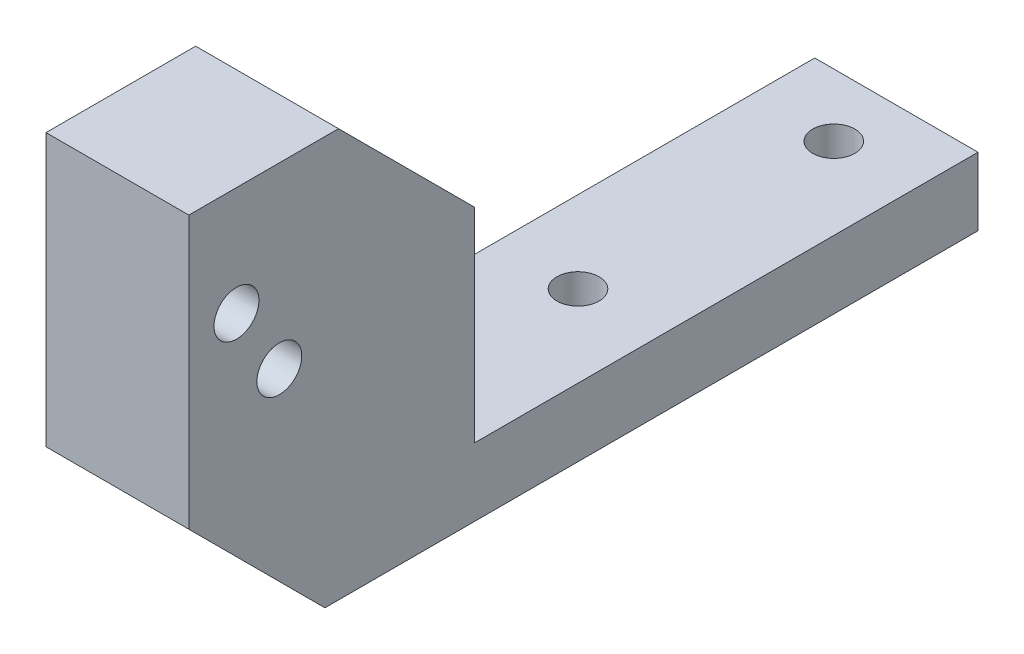
SolidWorks part; units mm, degrees
ref_plane "前视基准面" through (0, 0, 0) normal (0, 0, 1) x (1, 0, 0)
ref_plane "上视基准面" through (0, 0, 0) normal (0, 1, 0) x (1, 0, 0)
ref_plane "右视基准面" through (0, 0, 0) normal (1, 0, 0) x (0, 0, -1)
sketch "草图1" plane through (0, 0, 0) normal (0, 1, 0) x (1, 0, 0)
  line L0 (-55, 0) -> (55, 0) construction
  line L1 (-6, -14) -> (6, -14)
  line L2 (-6, -14) -> (-6, 14)
  line L3 (-6, 14) -> (6, 14)
  line L4 (6, -14) -> (6, 14)
  line L5 (-6, -14) -> (6, 14) construction
  line L6 (-6, 14) -> (6, -14) construction
  circle A0 centre (0, 9.4) radius 1.55
  circle A1 centre (0, -9.4) radius 1.55
  point P0 (0, 0)
  dimension "D3" = 18.8
  dimension "D4" = 3.1
  dimension "D1" = 28
  dimension "D2" = 12
extrude "凸台-拉伸1" add sketch "草图1" along normal mid plane 5
sketch "草图2" plane through (0, 0, 14) normal (0, 0, 1) x (1, 0, 0)
  line L1 (-6, 2.5) -> (6, 2.5)
  line L2 (-6, 2.5) -> (-6, -2.5)
  line L3 (-6, -2.5) -> (6, -2.5)
  line L4 (6, 2.5) -> (6, -2.5)
extrude "凸台-拉伸2" add sketch "草图2" along normal blind 30
sketch "草图3" plane through (0, 2.5, 0) normal (0, 1, 0) x (1, 0, 0)
  line L1 (6, -44) -> (-4.5, -44)
  line L2 (6, -44) -> (6, -23)
  line L3 (6, -23) -> (-4.5, -23)
  line L4 (-4.5, -44) -> (-4.5, -23)
  dimension "D1" = 21
  dimension "D2" = 10.5
extrude "凸台-拉伸3" add sketch "草图3" along normal blind 25
chamfer "倒角1" distance 10 angle 45 1 edges at (0.75, 27.5, 23)
sketch "草图4" plane through (-4.5, 0, 0) normal (-1, 0, 0) x (0, 0, 1)
  line L0 (44, 27.5) -> (44, 2.5) construction
  line L1 (33, 27.5) -> (44, 27.5) construction
  circle A0 centre (40.5, 19.5) radius 1.65
  circle A1 centre (37.35, 14.3934) radius 1.65
  dimension "D1" = 3.3
  dimension "D2" = 3.3
  dimension "D3" = 6
  dimension "D4" = 3.5
  dimension "D6" = 6.65
  dimension "D5" = 8
extrude "切除-拉伸1" cut sketch "草图4" against normal blind 25
chamfer "倒角2" distance 10 angle 45 1 edges at (0, -2.5, 44)
